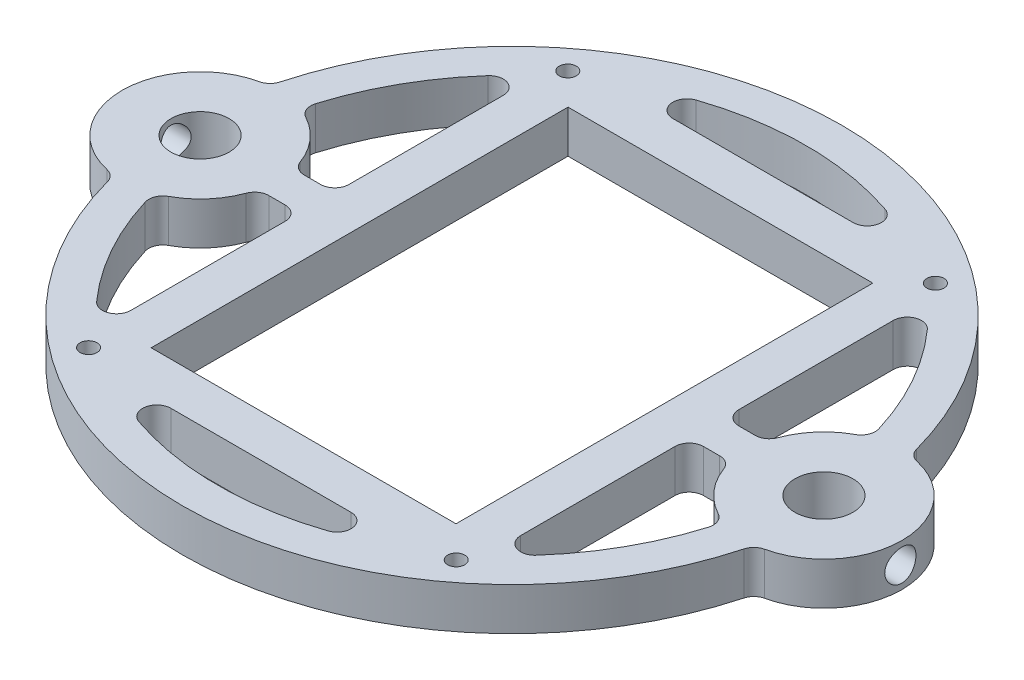
SolidWorks part; units mm, degrees
ref_plane "Front Plane" through (0, 0, 0) normal (0, 0, 1) x (1, 0, 0)
ref_plane "Top Plane" through (0, 0, 0) normal (0, 1, 0) x (1, 0, 0)
ref_plane "Right Plane" through (0, 0, 0) normal (1, 0, 0) x (0, 0, -1)
sketch "Sketch1" plane through (0, 0, 0) normal (0, 1, 0) x (1, 0, 0)
  circle A0 centre (0, 0) radius 12.7
  circle A1 centre (0, 0) radius 3.3528
  dimension "D1" = 25.4
  dimension "D2" = 6.7056
extrude "Boss-Extrude1" add sketch "Sketch1" along normal mid plane 7.62
sketch "Sketch2" plane through (0, 0, 0) normal (0, 1, 0) x (1, 0, 0)
  line L0 (12.2967, 3.175) -> (42.2756, 3.175)
  line L1 (12.2967, -3.175) -> (42.2756, -3.175)
  circle A0 centre (0, 0) radius 12.7 construction
  arc A1 (42.2756, -3.175) -> (42.2756, 3.175) centre (55.88, 0) ccw
  circle A3 centre (55.88, 0) radius 5.207
  arc A4 (12.2967, -3.175) -> (12.2967, 3.175) centre (0, 0) ccw
  dimension "D2" = 13.97
  dimension "D3" = 6.35
  dimension "D1" = 10.414
  dimension "D4" = 55.88
extrude "Boss-Extrude2" add sketch "Sketch2" along normal mid plane 7.62
ref_plane "Plane1" through (69.85, 0, 0) normal (1, 0, 0) x (0, 0, -1)
sketch "Sketch3" plane through (69.85, 0, 0) normal (1, 0, 0) x (0, 0, -1)
  circle A0 centre (0, 0) radius 2.794
  dimension "D1" = 5.588
extrude "Cut-Extrude1" cut sketch "Sketch3" against normal up to next
mirror "Mirror1" about plane through (0, 0, 0) normal (1, 0, 0) of "Cut-Extrude1", "Boss-Extrude2"
sketch "Sketch4" plane through (0, 0, 0) normal (0, 1, 0) x (1, 0, 0)
  circle A0 centre (0, 0) radius 55.88 construction
  arc A1 (-57.3989, -13.8872) -> (57.3989, -13.8872) centre (0, 0) ccw
  arc A2 (-51.0489, -13.1081) -> (51.0489, -13.1081) centre (0, 0) ccw
  arc A3 (42.2756, -3.175) -> (42.2756, 3.175) centre (55.88, 0) ccw construction
  arc A4 (-42.2756, 3.175) -> (-42.2756, -3.175) centre (-55.88, 0) ccw construction
  arc A5 (42.2756, -3.175) -> (42.2756, 3.175) centre (55.88, 0) ccw
  arc A6 (-42.2756, 3.175) -> (-42.2756, -3.175) centre (-55.88, 0) ccw
  arc A7 (51.0489, 13.1081) -> (-51.0489, 13.1081) centre (0, 0) ccw
  circle A8 centre (0, 0) radius 59.055 construction
  circle A9 centre (0, 0) radius 52.705 construction
  arc A10 (57.3989, 13.8872) -> (-57.3989, 13.8872) centre (0, 0) ccw
  point P4 (52.7134, 0.9672)
  point P13 (59.0634, 0.9672)
  dimension "D1" = 3.175
  dimension "D2" = 3.175
extrude "Boss-Extrude3" add sketch "Sketch4" along normal mid plane 7.62 contours A6 A1 A5 A2 | A5 A10 A6 A7
fillet "Fillet1" radius 2.54 16 edges at (12.2967, 0, -3.175) (12.2967, 0, 3.175) (42.2756, 0, -3.175) (42.2756, 0, 3.175) (57.3989, 0, -13.8872) (57.3989, 0, 13.8872) (51.0489, 0, -13.1081) (51.0489, 0, 13.1081) (-57.3989, 0, -13.8872) (-57.3989, 0, 13.8872) (-51.0489, 0, 13.1081) (-42.2756, 0, -3.175) (-42.2756, 0, 3.175) (-51.0489, 0, -13.1081) (-12.2967, 0, -3.175) (-12.2967, 0, 3.175)
sketch "Sketch5" plane through (0, 0, 0) normal (0, 1, 0) x (1, 0, 0)
  line L0 (-27.305, 37.338) -> (27.305, 37.338)
  line L5 (-34.925, -44.958) -> (34.925, -44.958)
  line L6 (-34.925, -44.958) -> (-34.925, 44.958)
  line L7 (-34.925, 44.958) -> (34.925, 44.958)
  line L8 (34.925, -44.958) -> (34.925, 44.958)
  line L9 (-34.925, -44.958) -> (34.925, 44.958) construction
  line L10 (-34.925, 44.958) -> (34.925, -44.958) construction
  line L11 (27.305, -37.338) -> (27.305, 37.338)
  line L12 (-27.305, -37.338) -> (27.305, -37.338)
  line L13 (-27.305, -37.338) -> (-27.305, 37.338)
  point P0 (0, 0)
  dimension "D1" = 69.85
  dimension "D2" = 89.916
  dimension "D3" = 7.62
extrude "Boss-Extrude4" add sketch "Sketch5" along normal mid plane 7.62
sketch "Sketch6" plane through (0, 0, 0) normal (0, 1, 0) x (1, 0, 0)
  line L1 (-27.305, 37.338) -> (27.305, 37.338)
  line L2 (-27.305, 37.338) -> (-27.305, -37.338)
  line L3 (-27.305, -37.338) -> (27.305, -37.338)
  line L4 (27.305, 37.338) -> (27.305, -37.338)
  line L5 (-27.305, 37.338) -> (27.305, -37.338) construction
  line L6 (-27.305, -37.338) -> (27.305, 37.338) construction
  point P0 (0, 0)
extrude "Cut-Extrude2" cut sketch "Sketch6" against normal through all both and the other way through all
sketch "Sketch7" plane through (0, 3.81, 0) normal (0, 1, 0) x (1, 0, 0)
  line L1 (-32.9311, 42.926) -> (32.9311, 42.926) construction
  line L2 (-32.9311, 42.926) -> (-32.9311, -42.926) construction
  line L3 (-32.9311, -42.926) -> (32.9311, -42.926) construction
  line L4 (32.9311, 42.926) -> (32.9311, -42.926) construction
  line L5 (-32.9311, 42.926) -> (32.9311, -42.926) construction
  line L6 (-32.9311, -42.926) -> (32.9311, 42.926) construction
  circle A0 centre (-32.9311, 42.926) radius 1.524
  circle A1 centre (32.9311, 42.926) radius 1.524
  circle A2 centre (32.9311, -42.926) radius 1.524
  circle A3 centre (-32.9311, -42.926) radius 1.524
  point P0 (0, 0)
  dimension "D3" = 3.048
  dimension "D1" = 85.852
  dimension "D2" = 65.8622
fillet "Fillet2" radius 2.54 12 edges at (-27.5063, 0, -44.958) (27.5063, 0, -44.958) (-34.925, 0, -39.4723) (-34.925, 0, -3.175) (-34.925, 0, 3.175) (34.925, 0, -39.4723) (34.925, 0, -3.175) (34.925, 0, 3.175) (34.925, 0, 39.4723) (27.5063, 0, 44.958) (-27.5063, 0, 44.958) (-34.925, 0, 39.4723)
extrude "Cut-Extrude3" cut sketch "Sketch7" against normal up to next and the other way through all contours A0 | A1 | A2 | A3
